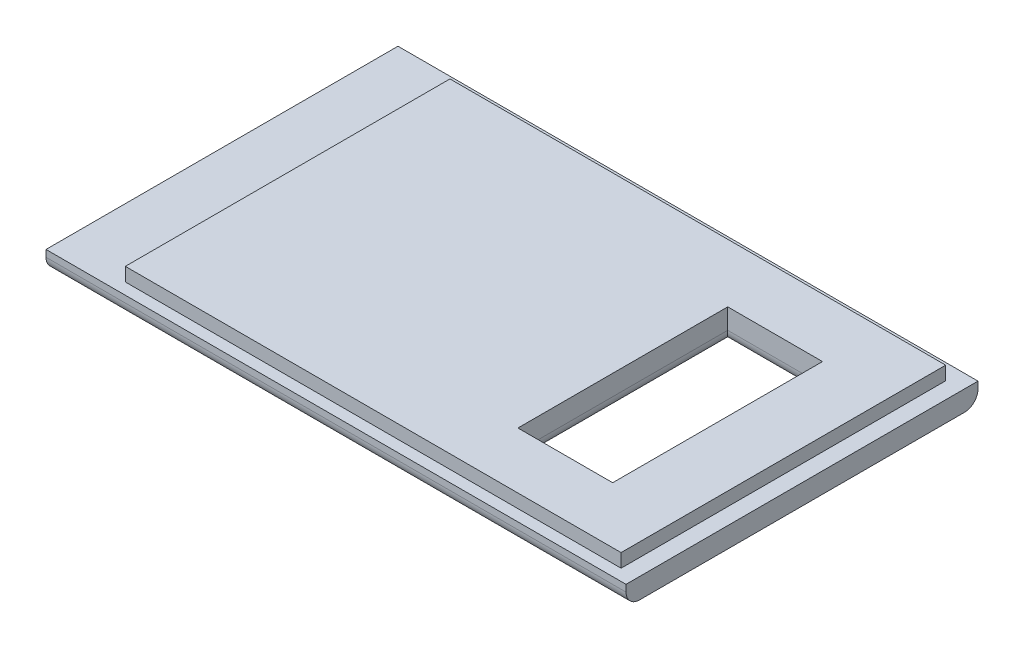
SolidWorks part; units mm, degrees
ref_plane "Front Plane" through (0, 0, 0) normal (0, 0, 1) x (1, 0, 0)
ref_plane "Top Plane" through (0, 0, 0) normal (0, 1, 0) x (1, 0, 0)
ref_plane "Right Plane" through (0, 0, 0) normal (1, 0, 0) x (0, 0, -1)
sketch "Sketch1" plane through (0, 0, 0) normal (0, 1, 0) x (1, 0, 0)
  line L13 (-42.525, 46.2472) -> (66.2991, 46.2472)
  line L14 (-42.525, 46.2472) -> (-42.525, -19.7928)
  line L15 (-42.525, -19.7928) -> (66.2991, -19.7928)
  line L16 (66.2991, 46.2472) -> (66.2991, -19.7928)
extrude "Boss-Extrude1" add sketch "Sketch1" along normal blind 3.81 contours L13 L16 L15 L14
sketch "Sketch5" plane through (0, 3.81, 0) normal (0, 1, 0) x (1, 0, 0)
  line L0 (-29.7959, 43.2706) -> (63.2189, 43.2706)
  line L1 (-29.7959, 43.2706) -> (-29.7959, -17.6386)
  line L2 (-29.7959, -17.6386) -> (63.2189, -17.6386)
  line L3 (63.2189, 43.2706) -> (63.2189, -17.6386)
  line L4 (58.7149, 38.6245) -> (31.1051, 38.6245)
  line L5 (58.7149, 38.6245) -> (58.7149, -14.5936)
  line L6 (58.7149, -14.5936) -> (31.1051, -14.5936)
  line L7 (31.1051, 38.6245) -> (31.1051, -14.5936)
  line L8 (-26.1972, 25.6449) -> (27.1428, 25.6449)
  line L9 (-26.1972, 25.6449) -> (-26.1972, -1.0251)
  line L10 (-26.1972, -1.0251) -> (27.1428, -1.0251)
  line L11 (27.1428, 25.6449) -> (27.1428, -1.0251)
  line L13 (-42.5849, 46.0675) -> (66.2392, 46.0675)
  line L14 (-42.5849, 46.0675) -> (-42.5849, -19.9725)
  line L15 (-42.5849, -19.9725) -> (66.2392, -19.9725)
  line L16 (66.2392, 46.0675) -> (66.2392, -19.9725)
extrude "Boss-Extrude2" add sketch "Sketch5" along normal blind 2.54 contours L0 L3 L2 L1
fillet "Fillet1" radius 2.54 2 edges at (11.887, 0, -46.2472) (11.887, 0, 19.7928)
sketch "Sketch6" plane through (0, 6.35, 0) normal (0, 1, 0) x (1, 0, 0)
  line L1 (33.2999, 32.2924) -> (51.0799, 32.2924)
  line L2 (33.2999, 32.2924) -> (33.2999, -7.0776)
  line L3 (33.2999, -7.0776) -> (51.0799, -7.0776)
  line L4 (51.0799, 32.2924) -> (51.0799, -7.0776)
extrude "Cut-Extrude1" cut sketch "Sketch6" against normal blind 7.366 contours L2 L3 L4 L1
fillet "Fillet2" radius 2.54 4 edges at (42.1899, 0, -32.2924) (33.2999, 0, -12.6074) (42.1899, 0, 7.0776) (51.0799, 0, -12.6074)
